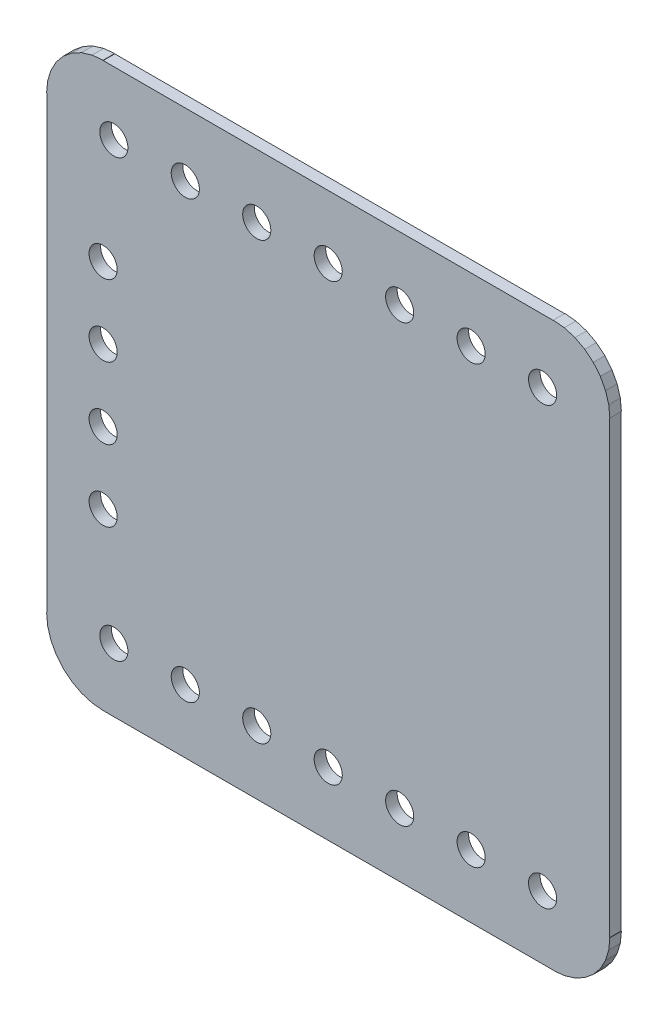
SolidWorks part; units mm, degrees
ref_plane "前视基准面" through (0, 0, 0) normal (0, 0, 1) x (1, 0, 0)
ref_plane "上视基准面" through (0, 0, 0) normal (0, 1, 0) x (1, 0, 0)
ref_plane "右视基准面" through (0, 0, 0) normal (1, 0, 0) x (0, 0, -1)
ref_plane "基准面4" through (0, 0, 0) normal (0, 0, -1) x (-1, 0, 0)
sketch "草图1" plane through (0, 0, 0) normal (0, 0, -1) x (-1, 0, 0)
  line L0 (-4.1433, 3.231) -> (-4.0289, 3.608)
  line L1 (-4.0289, 3.608) -> (-3.9903, 4)
  line L2 (-3.9903, 4) -> (-4, 4)
  line L3 (-4, 4) -> (-4, 20)
  line L4 (-4, 20) -> (-3.9903, 20)
  line L5 (-3.9903, 20) -> (-4.0289, 20.3921)
  line L6 (-4.0289, 20.3921) -> (-4.1433, 20.7691)
  line L7 (-4.1433, 20.7691) -> (-4.329, 21.1165)
  line L8 (-4.329, 21.1165) -> (-4.5789, 21.4211)
  line L9 (-4.5789, 21.4211) -> (-4.8835, 21.671)
  line L10 (-4.8835, 21.671) -> (-5.2309, 21.8567)
  line L11 (-5.2309, 21.8567) -> (-5.6079, 21.9711)
  line L12 (-5.6079, 21.9711) -> (-6, 22.0097)
  line L13 (-6, 22.0097) -> (-6, 22)
  line L14 (-6, 22) -> (-22, 22)
  line L15 (-22, 22) -> (-22, 22.0097)
  line L16 (-22, 22.0097) -> (-22.3921, 21.9711)
  line L17 (-22.3921, 21.9711) -> (-22.7691, 21.8567)
  line L18 (-22.7691, 21.8567) -> (-23.1165, 21.671)
  line L19 (-23.1165, 21.671) -> (-23.4211, 21.4211)
  line L20 (-23.4211, 21.4211) -> (-23.671, 21.1165)
  line L21 (-23.671, 21.1165) -> (-23.8567, 20.7691)
  line L22 (-23.8567, 20.7691) -> (-23.9711, 20.3921)
  line L23 (-23.9711, 20.3921) -> (-24.0097, 20)
  line L24 (-24.0097, 20) -> (-24, 20)
  line L25 (-24, 20) -> (-24, 4)
  line L26 (-24, 4) -> (-24.0097, 4)
  line L27 (-24.0097, 4) -> (-23.9711, 3.6079)
  line L28 (-23.9711, 3.6079) -> (-23.8567, 3.2309)
  line L29 (-23.8567, 3.2309) -> (-23.671, 2.8835)
  line L30 (-23.671, 2.8835) -> (-23.4211, 2.5789)
  line L31 (-23.4211, 2.5789) -> (-23.1165, 2.329)
  line L32 (-23.1165, 2.329) -> (-22.7691, 2.1433)
  line L33 (-22.7691, 2.1433) -> (-22.3921, 2.0289)
  line L34 (-22.3921, 2.0289) -> (-22, 1.9903)
  line L35 (-22, 1.9903) -> (-22, 2)
  line L36 (-22, 2) -> (-6, 1.9903)
  line L37 (-6, 1.9903) -> (-5.6079, 2.029)
  line L38 (-5.6079, 2.029) -> (-5.2309, 2.1433)
  line L39 (-5.2309, 2.1433) -> (-4.8835, 2.329)
  line L40 (-4.8835, 2.329) -> (-4.5789, 2.579)
  line L41 (-4.5789, 2.579) -> (-4.329, 2.8835)
  line L42 (-4.329, 2.8835) -> (-4.1433, 3.231)
  circle A0 centre (-19.08, 19.75) radius 0.5
  circle A1 centre (-16.54, 19.75) radius 0.5
  circle A2 centre (-21.62, 19.75) radius 0.5
  circle A3 centre (-11.46, 19.75) radius 0.5
  circle A4 centre (-14, 19.75) radius 0.5
  circle A5 centre (-19.08, 4.25) radius 0.5
  circle A6 centre (-21.62, 4.25) radius 0.5
  circle A7 centre (-14, 4.25) radius 0.5
  circle A8 centre (-16.54, 4.25) radius 0.5
  circle A9 centre (-8.92, 19.75) radius 0.5
  circle A10 centre (-6.38, 19.75) radius 0.5
  circle A11 centre (-6, 15.81) radius 0.5
  circle A12 centre (-6, 13.27) radius 0.5
  circle A13 centre (-6, 10.73) radius 0.5
  circle A14 centre (-8.92, 4.25) radius 0.5
  circle A15 centre (-11.46, 4.25) radius 0.5
  circle A16 centre (-6, 8.19) radius 0.5
  circle A17 centre (-6.38, 4.25) radius 0.5
extrude "凸台-拉伸1" add sketch "草图1" against normal blind 0.4115
sketch "草图2" plane through (0, 0, 0.4115) normal (0, 0, 1) x (1, 0, 0)
  line L0 (79.319, 238.4582) -> (383.9857, 238.4582) construction
sketch "草图3" plane through (0, 0, 0) normal (0, 0, -1) x (-1, 0, 0)
  line L0 (48.6258, 226.0448) -> (341.9591, 226.0448) construction
